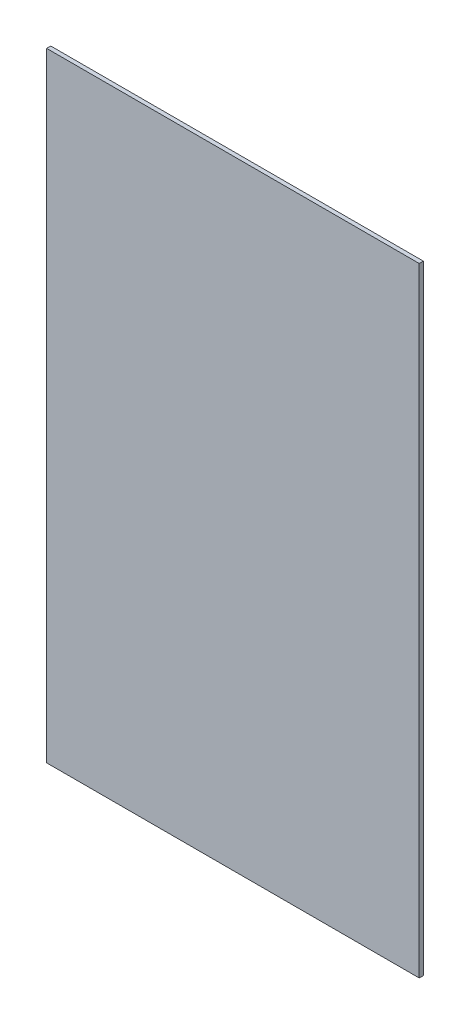
SolidWorks part; units mm, degrees
ref_plane "前视基准面" through (0, 0, 0) normal (0, 0, 1) x (1, 0, 0)
ref_plane "上视基准面" through (0, 0, 0) normal (0, 1, 0) x (1, 0, 0)
ref_plane "右视基准面" through (0, 0, 0) normal (1, 0, 0) x (0, 0, -1)
sketch "草图1" plane through (0, 0, 0) normal (0, 0, 1) x (1, 0, 0)
  line L1 (-227, -377) -> (227, -377)
  line L2 (-227, -377) -> (-227, 377)
  line L3 (-227, 377) -> (227, 377)
  line L4 (227, -377) -> (227, 377)
  line L5 (-227, -377) -> (227, 377) construction
  line L6 (-227, 377) -> (227, -377) construction
  point P0 (0, 0)
  point P6 (-230, -261.2531)
  dimension "D1" = 454
  dimension "D2" = 754
extrude "凸台-拉伸1" add sketch "草图1" along normal blind 5
